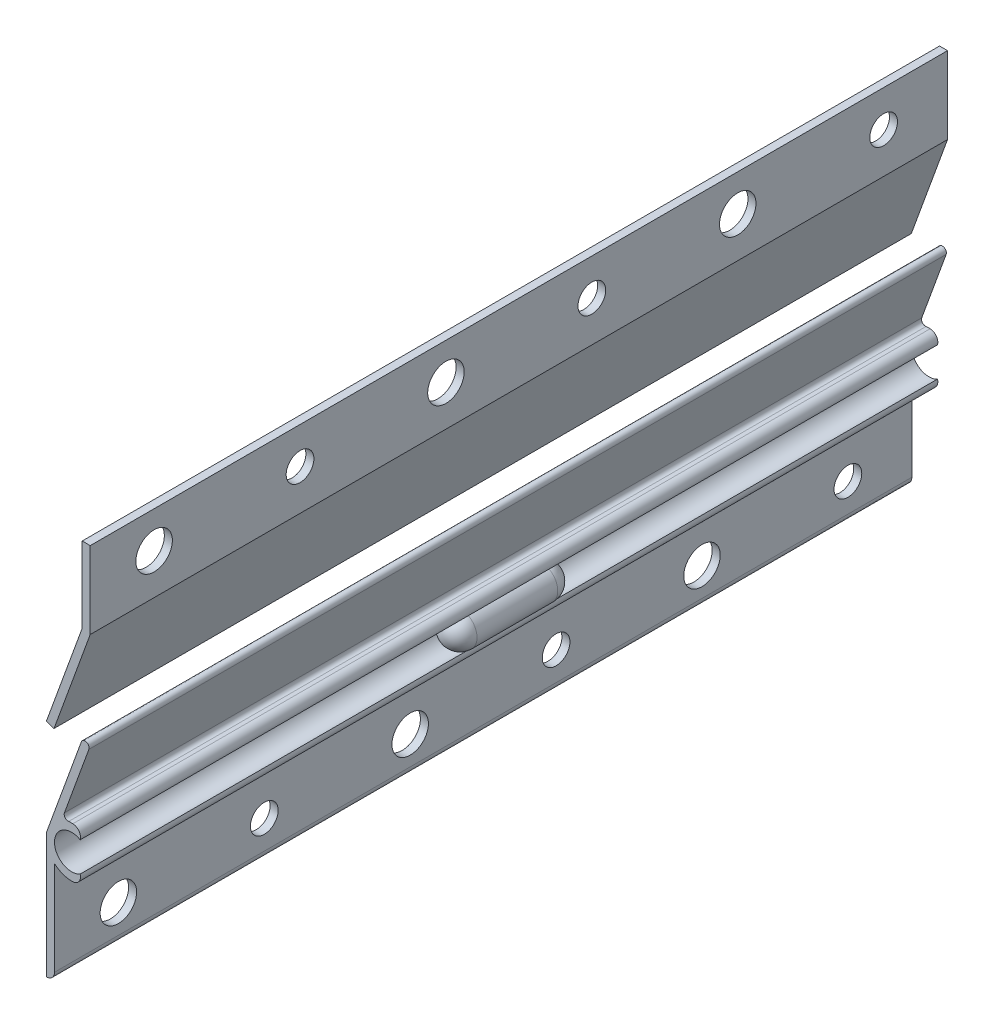
SolidWorks part; units mm, degrees
ref_plane "Front Plane" through (0, 0, 0) normal (0, 0, 1) x (1, 0, 0)
ref_plane "Top Plane" through (0, 0, 0) normal (0, 1, 0) x (1, 0, 0)
ref_plane "Right Plane" through (0, 0, 0) normal (1, 0, 0) x (0, 0, -1)
sketch "Sketch1" plane through (0, 0, 0) normal (0, 0, 1) x (1, 0, 0)
  line L0 (-3.81, -28.067) -> (-3.81, -6.2738) construction
  line L2 (-3.81, -28.067) -> (-2.413, -28.067) construction
  line L3 (-2.413, -28.067) -> (-2.413, -6.5201) construction
  line L4 (-2.413, -6.5201) -> (3.81, 10.5775) construction
  line L5 (3.81, 10.5775) -> (2.4972, 11.0553) construction
  line L6 (2.413, 28.067) -> (3.81, 28.067) construction
  line L7 (3.81, 28.067) -> (3.81, 14.662) construction
  line L9 (-2.4972, -2.667) -> (-3.81, -2.1892) construction
  line L10 (-3.81, -2.1892) -> (2.413, 14.9084) construction
  line L11 (2.413, 14.9084) -> (2.413, 28.067) construction
  line L12 (-3.81, -6.2738) -> (3.81, 14.662) construction
  line L13 (0, 28.067) -> (0, -28.067) construction
  line L14 (-3.81, 0) -> (3.81, 0) construction
  circle A0 centre (0.5689, -7.0459) radius 2.9819 construction
  circle A1 centre (0.5689, -7.0459) radius 4.3789 construction
  point P21 (0.5689, -2.667)
  dimension "Leaf Thickness" = 1.397
  dimension "Projection" = 7.62
  dimension "Length (C)" = 30.734
  dimension "Upper Leaf to Bottom" = 25.4
  dimension "D5" = 20
sketch "Sketch2" plane through (0, 0, 0) normal (1, 0, 0) x (0, 0, -1)
  line L0 (-74.6252, 28.067) -> (74.6252, 28.067) construction
  line L1 (-74.6252, 28.067) -> (-74.6252, 14.662) construction
  line L2 (-74.6252, 14.662) -> (74.6252, 14.662) construction
  line L3 (74.6252, 28.067) -> (74.6252, 14.662) construction
  line L4 (74.6252, -28.067) -> (-74.6252, -28.067) construction
  line L5 (74.6252, -28.067) -> (74.6252, -6.5201) construction
  line L6 (74.6252, -6.5201) -> (-74.6252, -6.5201) construction
  line L7 (-74.6252, -28.067) -> (-74.6252, -6.5201) construction
  line L8 (-12.7, 21.717) -> (12.7, 21.717) construction
  line L9 (0, 28.067) -> (0, -28.067) construction
  line L10 (-63.5, 21.717) -> (-63.5, 28.067) construction
  line L11 (-63.5, 21.717) -> (-38.1, 21.717) construction
  circle A0 centre (-63.5, 21.717) radius 3.175 construction
  circle A1 centre (-38.1, 21.717) radius 2.413 construction
  point P9 (152.4, 28.067)
  point P22 (0, -21.717)
  point P23 (0, 21.717)
  point P24 (-25.4, 21.717)
  point P25 (-50.8, 21.717)
  point P27 (25.4, 21.717)
  dimension "Large Mounting Hole" = 6.35
  dimension "Small Mounting Hole" = 4.826
  dimension "Length (A)" = 149.2504
  dimension "Hole Spacing" = 25.4
  dimension "Edge to Holes" = 6.35
  dimension "Number of Mounting Holes" = 304.8
  dimension "D5" = 6.35
  dimension "D1" = 50.8
  dimension "D2" = 25.4
  dimension "D3" = 38.1
sketch "Sketch3" plane through (0, 0, 0) normal (0, 0, 1) x (1, 0, 0)
  line L0 (-3.81, -2.1892) -> (-2.4972, -2.667)
  line L1 (-2.4972, -2.667) -> (3.81, 14.662)
  line L2 (3.81, 14.662) -> (3.81, 28.067)
  line L3 (3.81, 28.067) -> (2.413, 28.067)
  line L4 (2.413, 28.067) -> (2.413, 14.9084)
  line L5 (2.413, 14.9084) -> (-3.81, -2.1892)
extrude "Boss-Extrude1" add sketch "Sketch3" along normal up to vertex (74.6252 mm away) and the other way up to vertex (74.6252 mm away) up to point (0, 28.067, 74.6252) other way up to point (0, 28.067, -74.6252)
sketch "Sketch4" plane through (0, 0, 0) normal (0, 0, 1) x (1, 0, 0)
  line L0 (3.5711, 9.9211) -> (-0.6821, -1.7645)
  line L1 (-2.413, -10.2526) -> (-2.413, -26.67)
  line L3 (-3.81, -28.067) -> (-3.81, -6.2738)
  line L4 (-3.81, -6.2738) -> (2.2583, 10.3989)
  line L6 (-2.413, -6.5201) -> (3.81, 10.5775) construction
  line L7 (-3.81, -6.2738) -> (3.81, 14.662) construction
  line L8 (3.81, 10.5775) -> (2.4972, 11.0553) construction
  line L9 (-2.413, -28.067) -> (-2.413, -6.5201) construction
  line L10 (2.0598, -4.4635) -> (0.5689, -7.0459) construction
  arc A0 (2.2583, 10.3989) -> (3.5711, 9.9211) centre (2.9147, 10.16) cw
  arc A1 (-3.81, -28.067) -> (-2.413, -26.67) centre (-3.81, -26.67) ccw
  arc A3 (2.0598, -4.4635) -> (2.0598, -9.6282) centre (0.5689, -7.0459) ccw
  circle A4 centre (0.5689, -7.0459) radius 2.9819 construction
  arc A5 (-2.413, -10.2526) -> (0.7908, -11.4191) centre (0.5689, -7.0459) ccw
  arc A7 (2.0598, -9.6282) -> (0.7908, -11.4191) centre (0.72, -10.0239) cw
  arc A9 (-0.6821, -1.7645) -> (0.0561, -2.6971) centre (-0.0257, -2.0034) ccw
  arc A10 (0.0561, -2.6971) -> (0.7908, -2.6726) centre (0.5689, -7.0459) cw
  circle A11 centre (0.5689, -7.0459) radius 4.3789 construction
  arc A12 (2.0598, -4.4635) -> (0.7908, -2.6726) centre (0.72, -4.0678) ccw
  dimension "D1" = 60
extrude "Boss-Extrude2" add sketch "Sketch4" along normal up to vertex (74.6252 mm away) and the other way up to vertex (74.6252 mm away) separate body up to point (0, -6.5201, 74.6252) other way up to point (0, -6.5201, -74.6252)
ref_plane "Plane1" through (0.5689, 0, 0) normal (1, 0, 0) x (0, 0, -1)
sketch "Sketch5" plane through (0.5689, 0, 0) normal (1, 0, 0) x (0, 0, -1)
  line L0 (-10.0077, -7.0459) -> (10.0077, -7.0459)
  line L3 (-7.0259, -4.064) -> (-2.342, -4.064)
  line L4 (-2.342, -4.064) -> (2.342, -4.064)
  line L9 (10.0077, -7.0459) -> (30.0232, -7.0459) construction
  line L10 (2.342, -4.064) -> (7.0259, -4.064)
  arc A4 (-10.0077, -7.0459) -> (-7.0259, -4.064) centre (-7.0259, -7.0459) cw
  arc A5 (10.0077, -7.0459) -> (7.0259, -4.064) centre (7.0259, -7.0459) ccw
  point P0 (0, -4.064)
revolve "Revolve1" add sketch "Sketch5" angle 360 about L9
sketch "Sketch6" plane through (0, 0, 0) normal (1, 0, 0) x (0, 0, -1)
  line L0 (-63.5, 21.717) -> (-38.1, 21.717) construction
  line L1 (-63.5, 21.717) -> (-38.1, 21.717) construction
  circle A0 centre (-63.5, 21.717) radius 3.175
  circle A1 centre (-38.1, 21.717) radius 2.413
  circle A2 centre (-38.1, 21.717) radius 2.413 construction
  circle A3 centre (-63.5, 21.717) radius 3.175 construction
extrude "Cut-Extrude1" cut sketch "Sketch6" against normal through all both and the other way through all
pattern_linear "LPattern1" count 3 spacing 50.8 along (0, 0, -1) of "Cut-Extrude1"
sketch "Sketch7" plane through (0, 0, 0) normal (1, 0, 0) x (0, 0, -1)
  line L0 (-63.5, -21.717) -> (-38.1, -21.717) construction
  line L1 (-63.5, 21.717) -> (-38.1, 21.717) construction
  circle A0 centre (-63.5, -21.717) radius 3.175
  circle A1 centre (-38.1, -21.717) radius 2.413
  circle A2 centre (-38.1, 21.717) radius 2.413 construction
  circle A3 centre (-63.5, 21.717) radius 3.175 construction
extrude "Cut-Extrude2" cut sketch "Sketch7" against normal through all both and the other way through all
pattern_linear "LPattern2" count 3 spacing 50.8 along (0, 0, -1) of "Cut-Extrude2"
move or copy body "Body-Move/Copy2" bodies to move or copy 108 copy no translate (0, 6.35, 0)
move or copy body "Body-Move/Copy3" bodies to move or copy 106 110 copy no translate (0, -6.35, 0)
equation "\"D5@Sketch2\" = \"Edge to Holes@Sketch2\""
equation "\"D3@LPattern1\" = \"Hole Spacing@Sketch2\" * 2"
equation "\"D1@LPattern1\"=(\"Number of Mounting Holes@Sketch2\"/4)"
equation "\"D3@LPattern2\"=\"D3@LPattern1\""
equation "\"D1@LPattern2\"=\"D1@LPattern1\""
equation "\"D1@Sketch2\"=\"Hole Spacing@Sketch2\"*((\"Number of Mounting Holes@Sketch2\"/4)-1)"
equation "\"D2@Sketch2\"=\"Hole Spacing@Sketch2\""
equation "\"D3@Sketch2\"=\"D1@Sketch2\"-(\"Hole Spacing@Sketch2\"/2)"
